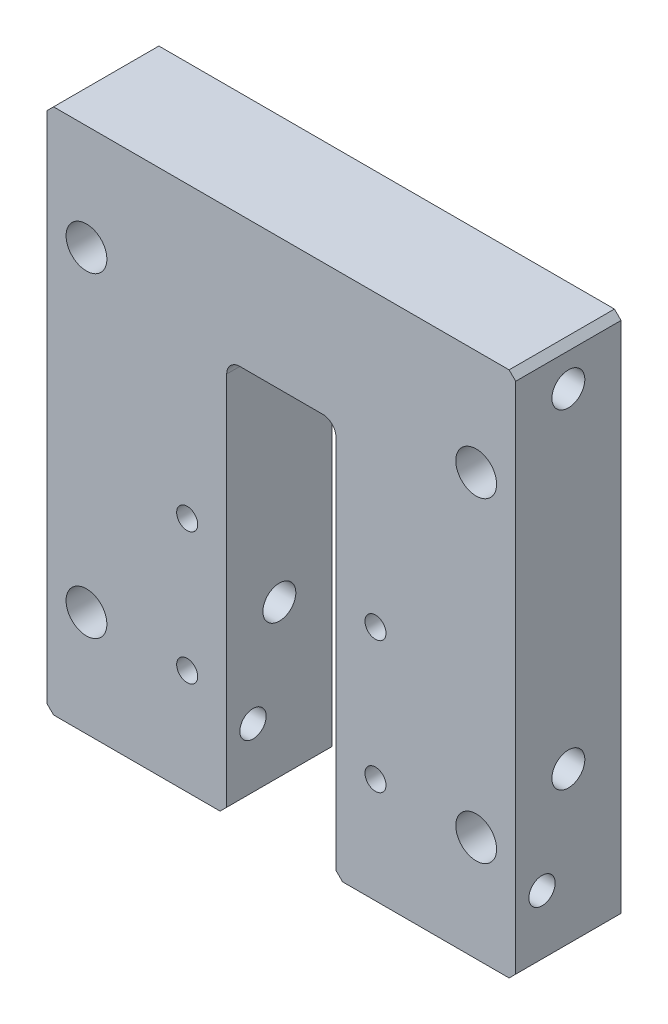
SolidWorks part; units mm, degrees
material "6061 合金"
ref_plane "前视基准面" through (0, 0, 0) normal (0, 0, 1) x (1, 0, 0)
ref_plane "上视基准面" through (0, 0, 0) normal (0, 1, 0) x (1, 0, 0)
ref_plane "右视基准面" through (0, 0, 0) normal (1, 0, 0) x (0, 0, -1)
sketch "草图1" plane through (0, 0, 0) normal (0, 0, 1) x (1, 0, 0)
  line L1 (-17.8, -20) -> (17.8, -20)
  line L2 (-17.8, -20) -> (-17.8, 20)
  line L3 (-17.8, 20) -> (17.8, 20)
  line L4 (17.8, -20) -> (17.8, 20)
  line L5 (0, 20) -> (0, -20) construction
  line L6 (-17.8, 0) -> (17.8, 0) construction
  point P0 (0, 0)
  dimension "D1" = 35.6
  dimension "D2" = 40
extrude "凸台-拉伸1" add sketch "草图1" along normal blind 8
sketch "草图2" plane through (0, 0, 8) normal (0, 0, 1) x (1, 0, 0)
  line L0 (17.8, 20) -> (-17.8, 20) construction
  line L1 (-14.8, -12) -> (14.8, -12) construction
  line L2 (-14.8, -12) -> (-14.8, 12) construction
  line L3 (-14.8, 12) -> (14.8, 12) construction
  line L4 (14.8, -12) -> (14.8, 12) construction
  line L5 (0, 12) -> (0, -12) construction
  line L6 (-14.8, 0) -> (14.8, 0) construction
  line L7 (17.8, -20) -> (17.8, 20) construction
  line L8 (-17.8, -20) -> (17.8, -20) construction
  circle A0 centre (14.8, 12) radius 1.55
  circle A1 centre (-14.8, 12) radius 1.55
  circle A2 centre (-14.8, -12) radius 1.55
  circle A3 centre (14.8, -12) radius 1.55
  point P0 (0, 0)
  dimension "D4" = 3.1
  dimension "D1" = 8
  dimension "D2" = 3
  dimension "D3" = 8
sketch "草图5" plane through (-17.8, 0, 0) normal (-1, 0, 0) x (0, 0, 1)
  circle A0 centre (6, -15) radius 1 construction
  circle A1 centre (6, -15) radius 1
extrude "切除-拉伸1" cut sketch "草图5" against normal blind 42
sketch "草图6" plane through (0, 0, 8) normal (0, 0, 1) x (1, 0, 0)
  line L0 (-17.8, -20) -> (17.8, -20) construction
  line L1 (-4.15, -50) -> (4.15, -50)
  line L2 (-4.15, -50) -> (-4.15, 10)
  line L3 (-4.15, 10) -> (4.15, 10)
  line L4 (4.15, -50) -> (4.15, 10)
  line L5 (0, 10) -> (0, -50) construction
  line L6 (-4.15, -20) -> (4.15, -20) construction
  point P0 (0, -20)
  dimension "D1" = 8.3
  dimension "D2" = 30
extrude "切除-拉伸2" cut sketch "草图6" against normal blind 10
extrude "切除-拉伸3" cut sketch "草图2" against normal blind 10
sketch "草图8" plane through (0, 0, 8) normal (0, 0, 1) x (1, 0, 0)
  line L0 (-7.15, -20) -> (-7.15, 10) construction
  line L1 (-17.8, -20) -> (-4.15, -20) construction
  line L2 (-4.15, 10) -> (-4.15, -20) construction
  line L3 (-7.15, 10) -> (-4.15, 10) construction
  dimension "D1" = 3
hole_wizard "M2 螺纹孔1" positions "草图9" profile "草图10" tap size "M2" standard "GB" end condition through all
sketch "草图9" plane through (0, 0, 8) normal (0, 0, 1) x (1, 0, 0)
  line L0 (-7.15, -20) -> (-7.15, 10) construction
  line L1 (-17.8, -20) -> (-4.15, -20) construction
  point P0 (-7.15, -12)
  point P4 (-7.15, -2)
  dimension "D1" = 8
  dimension "D2" = 10
sketch "草图10" plane through (-7.15, -12, 8) normal (1, 0, 0) x (0, -1, 0)
  line L0 (0, 0) -> (0, 8)
  line L1 (0, 8) -> (0.8, 8)
  line L2 (0.8, 8) -> (0.8, 0)
  line L5 (0.8, 0) -> (0, 0)
  line L11 (0, -6.35) -> (0, 107.95) construction
  dimension "通孔螺纹孔钻头直径" = 1.6
  dimension "通孔螺纹孔钻头深度" = 8
cosmetic thread "孔螺蚊线5" parameters "D2"=2
cosmetic thread "孔螺蚊线6" parameters "D2"=2
mirror "镜向1" about plane through (0, 0, 0) normal (1, 0, 0) of "M2 螺纹孔1"
cosmetic thread "孔螺蚊线7" parameters "D2"=2
cosmetic thread "孔螺蚊线8" parameters "D2"=2
sketch "草图11" plane through (-17.8, 0, 0) normal (-1, 0, 0) x (0, 0, 1)
  line L0 (4, 20) -> (4, -20) construction
  line L1 (8, 20) -> (0, 20) construction
  line L2 (8, -20) -> (0, -20) construction
hole_wizard "M3 螺纹孔2" positions "草图12" profile "草图13" tap size "M3" standard "GB" end condition through all
sketch "草图12" plane through (-17.8, 0, 0) normal (-1, 0, 0) x (0, 0, 1)
  line L0 (4, 20) -> (4, -20) construction
  line L1 (8, 20) -> (0, 20) construction
  line L2 (8, -20) -> (0, -20) construction
  point P0 (4, 17)
  point P4 (4, -8)
  dimension "D1" = 3
  dimension "D2" = 12
sketch "草图13" plane through (-17.8, 17, 4) normal (0, 1, 0) x (0, 0, 1)
  line L0 (0, 0) -> (0, 35.6)
  line L1 (0, 35.6) -> (1.25, 35.6)
  line L2 (1.25, 35.6) -> (1.25, 0)
  line L5 (1.25, 0) -> (0, 0)
  line L11 (0, -6.35) -> (0, 107.95) construction
  dimension "通孔螺纹孔钻头直径" = 2.5
  dimension "通孔螺纹孔钻头深度" = 35.6
cosmetic thread "孔螺蚊线9" parameters "D2"=3
cosmetic thread "孔螺蚊线10" parameters "D2"=3
fillet "圆角1" radius 1 2 edges at (4.15, 10, 4) (-4.15, 10, 4)
chamfer "倒角1" distance 0.5 angle 45 6 edges at (17.8, 20, 4) (17.8, -20, 4) (4.15, -20, 4) (-4.15, -20, 4) (-17.8, -20, 4) (-17.8, 20, 4)
